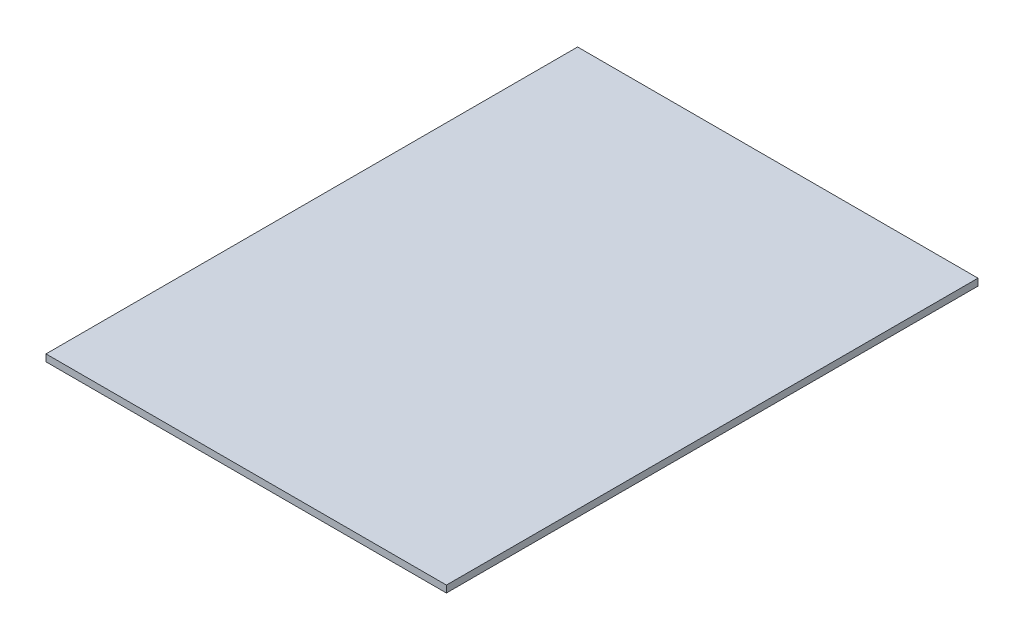
SolidWorks part; units mm, degrees
ref_plane "Спереди" through (0, 0, 0) normal (0, 0, 1) x (1, 0, 0)
ref_plane "Сверху" through (0, 0, 0) normal (0, 1, 0) x (1, 0, 0)
ref_plane "Справа" through (0, 0, 0) normal (1, 0, 0) x (0, 0, -1)
other "Configuration Table"
sketch "Эскиз1" plane through (0, 0, 0) normal (0, 1, 0) x (1, 0, 0)
  line L1 (29, -38.5) -> (-29, -38.5)
  line L2 (29, -38.5) -> (29, 38.5)
  line L3 (29, 38.5) -> (-29, 38.5)
  line L4 (-29, -38.5) -> (-29, 38.5)
  line L5 (29, -38.5) -> (-29, 38.5) construction
  line L6 (29, 38.5) -> (-29, -38.5) construction
  point P0 (0, 0)
  dimension "D1" = 58
  dimension "D2" = 77
extrude "Бобышка-Вытянуть1" add sketch "Эскиз1" along normal blind 1
